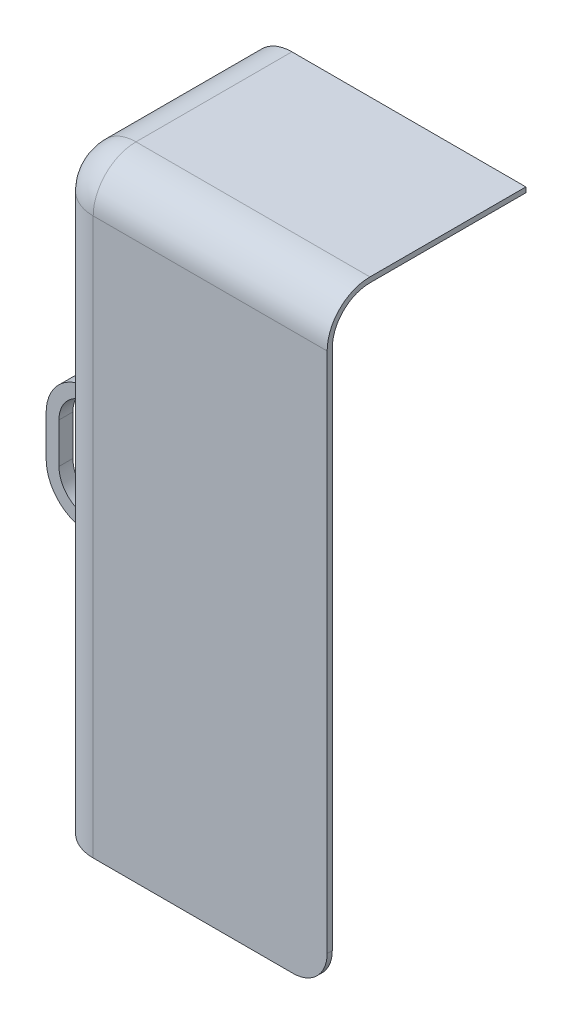
SolidWorks part; units mm, degrees
ref_plane "Front Plane" through (0, 0, 0) normal (0, 0, 1) x (1, 0, 0)
ref_plane "Top Plane" through (0, 0, 0) normal (0, 1, 0) x (1, 0, 0)
ref_plane "Right Plane" through (0, 0, 0) normal (1, 0, 0) x (0, 0, -1)
sketch "Sketch1" plane through (0, 0, 0) normal (0, 0, 1) x (1, 0, 0)
  line L0 (-7.6, 131.988) -> (-72.288, 131.988)
  line L1 (-7.6, 0) -> (-7.6, 232.4875) construction
  line L2 (-72.288, 131.988) -> (-72.288, -8)
  line L3 (-15.6, -8) -> (-179.5248, -8) construction
  line L4 (-72.288, -8) -> (-15.6, -8)
  line L5 (-7.6, 131.988) -> (-7.6, 0)
  line L6 (-57.288, 93.174) -> (-57.288, 57.614) construction
  line L7 (-50.7475, 128.988) -> (-41.54, 128.988) construction
  arc A0 (-15.6, -8) -> (-7.6, 0) centre (-15.6, 0) ccw construction
  arc A1 (-15.6, -8) -> (-7.6, 0) centre (-15.6, 0) ccw
  dimension "D1" = 15
  dimension "D2" = 3
extrude "Boss-Extrude1" add sketch "Sketch1" along normal offset from surface (46.45 mm away) 8
fillet "Fillet1" radius 10 1 edges at (-72.288, 131.988, 23.225)
fillet "Fillet2" radius 10 3 edges at (-34.944, 131.988, 46.45) (-72.288, 56.994, 46.45) (-69.3591, 129.0591, 46.45)
shell "Shell1" thickness 1.2
sketch "Sketch2" plane through (0, 0, 0) normal (0, 0, 1) x (1, 0, 0)
  line L0 (-76.288, 120.488) -> (-72.288, 120.488)
  line L1 (-72.288, 121.988) -> (-72.288, -8) construction
  line L2 (-72.288, 120.488) -> (-72.288, 113.488)
  line L3 (-72.288, 113.488) -> (-76.288, 113.488)
  line L4 (-62.288, 131.988) -> (-7.6, 131.988) construction
  line L5 (-76.288, 30.488) -> (-72.288, 30.488)
  line L6 (-72.288, 30.488) -> (-72.288, 23.488)
  line L7 (-72.288, 23.488) -> (-76.288, 23.488)
  circle A0 centre (-76.288, 116.988) radius 1.5
  arc A1 (-76.288, 120.488) -> (-76.288, 113.488) centre (-76.288, 116.988) ccw
  circle A2 centre (-76.288, 26.988) radius 1.5
  arc A3 (-76.288, 30.488) -> (-76.288, 23.488) centre (-76.288, 26.988) ccw
  dimension "D1" = 3
  dimension "D2" = 2
  dimension "D5" = 3
  dimension "D6" = 2
  dimension "D3" = 4
  dimension "D4" = 15
  dimension "D7" = 4
  dimension "D8" = 90
extrude "Boss-Extrude2" add sketch "Sketch2" along normal blind 2 from offset 10
sketch "Sketch3" plane through (-72.288, 0, 0) normal (-1, 0, 0) x (0, 0, 1)
  line L0 (0, -8) -> (13.45, -8) construction
  line L1 (36.45, -8) -> (0, -8) construction
  line L2 (0, 12) -> (13.45, 12)
  line L3 (0, -28) -> (13.45, -28)
  arc A0 (0, 12) -> (0, -28) centre (0, -8) ccw
  arc A1 (13.45, -28) -> (13.45, 12) centre (13.45, -8) ccw
  point P5 (6.725, -8)
  point P10 (13.8975, -8)
  point P13 (33.45, -8)
  dimension "D1" = 20
  dimension "D2" = 3
extrude "Cut-Extrude1" cut sketch "Sketch3" against normal up to surface (1.2 mm away) up to face at (-71.088, 56.994, 18.225)
sketch "Sketch4" plane through (-72.288, 0, 0) normal (-1, 0, 0) x (0, 0, 1)
  line L0 (36.45, -8) -> (36.45, 121.988) construction
  line L1 (36.45, 76.6836) -> (33.1975, 76.6836)
  line L2 (36.45, 76.6836) -> (36.45, 47.275)
  line L3 (36.45, 47.275) -> (33.1975, 47.275)
  line L4 (33.1975, 76.6836) -> (33.1975, 47.275)
extrude "Boss-Extrude3" add sketch "Sketch4" along normal blind 11
fillet "Fillet3" radius 10 2 edges at (-83.288, 47.275, 34.8238) (-83.288, 76.6836, 34.8238)
sketch "Sketch5" plane through (0, 0, 36.45) normal (0, 0, 1) x (1, 0, 0)
  line L8 (-80.288, 66.6836) -> (-80.288, 57.275)
  line L9 (-75.288, 50.5668) -> (-75.288, 73.3918)
  line L10 (-80.288, 66.6836) -> (-80.288, 57.275)
  line L11 (-75.288, 50.5668) -> (-75.288, 73.3918)
  arc A4 (-80.288, 57.275) -> (-75.288, 50.5668) centre (-73.288, 57.275) ccw
  arc A5 (-75.288, 73.3918) -> (-80.288, 66.6836) centre (-73.288, 66.6836) ccw
  arc A6 (-80.288, 57.275) -> (-75.288, 50.5668) centre (-73.288, 57.275) ccw
  arc A7 (-75.288, 73.3918) -> (-80.288, 66.6836) centre (-73.288, 66.6836) ccw
  dimension "D1" = 3
extrude "Cut-Extrude2" cut sketch "Sketch5" against normal up to surface (3.2525 mm away) up to face at (-76.9784, 61.9793, 33.1975)
